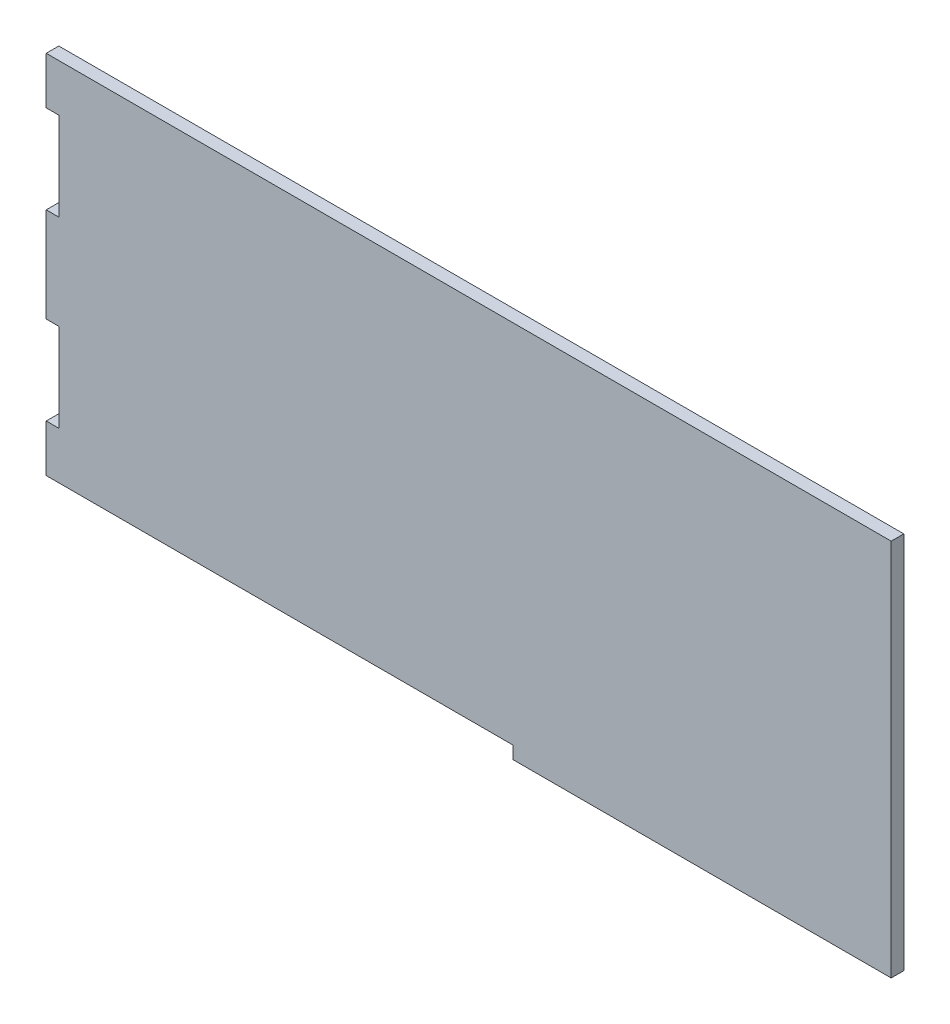
SolidWorks part; units mm, degrees
ref_plane "Alzado" through (0, 0, 0) normal (0, 0, 1) x (1, 0, 0)
ref_plane "Planta" through (0, 0, 0) normal (0, 1, 0) x (1, 0, 0)
ref_plane "Vista lateral" through (0, 0, 0) normal (1, 0, 0) x (0, 0, -1)
sketch "Croquis1" plane through (0, 0, 0) normal (0, 0, 1) x (1, 0, 0)
  line L0 (820, 0) -> (820, -363.7923) construction
  line L1 (0, 0) -> (185, 0)
  line L2 (0, 0) -> (0, 145)
  line L3 (0, 145) -> (1640, 145)
  line L4 (1640, 0) -> (1640, 145)
  line L5 (183.7346, 0) -> (185, 0)
  line L9 (485, -5) -> (185, -5)
  line L11 (670, 0) -> (670, -5)
  line L12 (670, -5) -> (970, -5)
  line L13 (970, 0) -> (970, -5)
  line L15 (1155, 0) -> (1155, -5)
  line L16 (1155, -5) -> (1455, -5)
  line L17 (1455, 0) -> (1455, -5)
  line L18 (185, 0) -> (185, -5)
  line L19 (485, 0) -> (481.1866, 0)
  line L20 (485, 0) -> (485, -5)
  line L21 (481.1866, 0) -> (670, 0)
  line L22 (970, 0) -> (1155, 0)
  line L23 (1455, 0) -> (1640, 0)
  point P15 (820, -5)
  dimension "D1" = 1640
  dimension "D2" = 145
  dimension "D3" = 5
  dimension "D4" = 185
  dimension "D5" = 300
  dimension "D6" = 300
  dimension "D7" = 5
  dimension "D8" = 185
extrude "Saliente-Extruir1" add sketch "Croquis1" along normal blind 5
sketch "Croquis2" plane through (0, 0, 5) normal (0, 0, 1) x (1, 0, 0)
  line L0 (1640, 72.5) -> (1561.7814, 72.5) construction
  line L1 (1640, 0) -> (1640, 145) construction
  line L2 (0, 145) -> (1640, 145) construction
  line L3 (1640, 126.25) -> (1635, 126.25)
  line L4 (1640, 126.25) -> (1640, 91.25)
  line L5 (1640, 91.25) -> (1635, 91.25)
  line L6 (1635, 126.25) -> (1635, 91.25)
  line L7 (1640, 53.75) -> (1635, 53.75)
  line L8 (1635, 18.75) -> (1635, 53.75)
  line L9 (1640, 18.75) -> (1635, 18.75)
  line L10 (1640, 18.75) -> (1640, 53.75)
  line L11 (820, 145) -> (820, 72.5) construction
  line L12 (0, 18.75) -> (0, 53.75)
  line L13 (0, 18.75) -> (5, 18.75)
  line L14 (5, 18.75) -> (5, 53.75)
  line L15 (0, 53.75) -> (5, 53.75)
  line L16 (0, 91.25) -> (5, 91.25)
  line L17 (5, 126.25) -> (5, 91.25)
  line L18 (0, 126.25) -> (5, 126.25)
  line L19 (0, 126.25) -> (0, 91.25)
  dimension "D1" = 35
  dimension "D2" = 18.75
  dimension "D3" = 5
extrude "Cortar-Extruir1" cut sketch "Croquis2" against normal blind 5 contours L7 L8 L9 L10 | L4 L3 L6 L5 | L16 L17 L18 L19 | L12 L15 L14 L13
sketch "Croquis3" plane through (0, 0, 5) normal (0, 0, 1) x (1, 0, 0)
  line L0 (577.5, 0) -> (577.5, 72.6456) construction
  line L1 (485, 0) -> (670, 0) construction
  line L2 (820, -5) -> (820, 72.6456) construction
  line L3 (670, -5) -> (970, -5) construction
  line L4 (579.3, 0) -> (575.7, 0)
  line L5 (575.7, 0) -> (575.7, 5)
  line L6 (575.7, 5) -> (573.9, 5)
  line L7 (573.9, 5) -> (573.9, 8.2)
  line L8 (573.9, 8.2) -> (575.7, 8.2)
  line L9 (575.7, 8.2) -> (575.7, 17.2)
  line L10 (575.7, 17.2) -> (579.3, 17.2)
  line L11 (579.3, 8.2) -> (579.3, 17.2)
  line L12 (581.1, 8.2) -> (579.3, 8.2)
  line L13 (581.1, 5) -> (581.1, 8.2)
  line L14 (579.3, 5) -> (581.1, 5)
  line L15 (579.3, 0) -> (579.3, 5)
  line L16 (1064.3, 8.2) -> (1064.3, 17.2)
  line L17 (1066.1, 8.2) -> (1064.3, 8.2)
  line L18 (1066.1, 5) -> (1066.1, 8.2)
  line L19 (1064.3, 5) -> (1066.1, 5)
  line L20 (1064.3, 0) -> (1064.3, 5)
  line L21 (1060.7, 0) -> (1064.3, 0)
  line L22 (1060.7, 0) -> (1060.7, 5)
  line L23 (1060.7, 5) -> (1058.9, 5)
  line L24 (1058.9, 5) -> (1058.9, 8.2)
  line L25 (1058.9, 8.2) -> (1060.7, 8.2)
  line L26 (1060.7, 8.2) -> (1060.7, 17.2)
  line L27 (1064.3, 17.2) -> (1060.7, 17.2)
  point P16 (577.5, 17.2)
  dimension "D1" = 1.8
  dimension "D2" = 5
  dimension "D3" = 1.8
  dimension "D4" = 3.2
  dimension "D5" = 1.8
  dimension "D6" = 9
extrude "Cortar-Extruir2" cut sketch "Croquis3" against normal blind 10 contours L10 L11 L12 L13 L14 L15 L4 L5 L6 L7 L8 L9 | L16 L27 L26 L25 L24 L23 L22 L21 L20 L19 L18 L17
sketch "Croquis4" plane through (0, 0, 5) normal (0, 0, 1) x (1, 0, 0)
  line L0 (335, -5) -> (335, 145)
  line L1 (485, -5) -> (185, -5) construction
  line L2 (0, 145) -> (1640, 145) construction
  line L3 (335, 145) -> (1640, 145)
  line L4 (1640, 145) -> (1671.1224, -141.5384)
  line L5 (1671.1224, -141.5384) -> (335, -87.5627)
  line L6 (335, -87.5627) -> (335, -5)
extrude "Cortar-Extruir4" cut sketch "Croquis4" against normal blind 10
